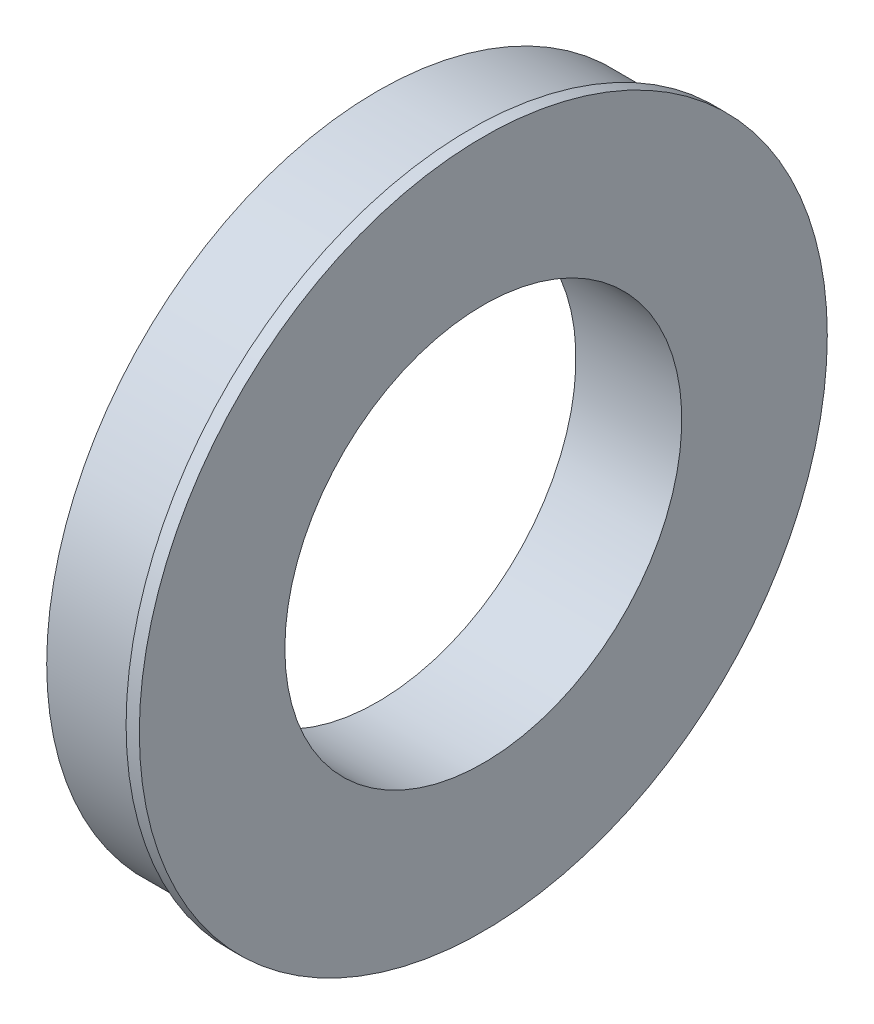
SolidWorks part; units mm, degrees
ref_plane "Front Plane" through (0, 0, 0) normal (0, 0, 1) x (1, 0, 0)
ref_plane "Top Plane" through (0, 0, 0) normal (0, 1, 0) x (1, 0, 0)
ref_plane "Right Plane" through (0, 0, 0) normal (1, 0, 0) x (0, 0, -1)
sketch "Sketch1" plane through (0, 0, 0) normal (1, 0, 0) x (0, 0, -1)
  circle A0 centre (0, 0) radius 38.1
  circle A1 centre (0, 0) radius 63.5
  dimension "D1" = 127
  dimension "D2" = 76.2
extrude "Boss-Extrude1" add sketch "Sketch1" along normal mid plane 19.05
sketch "Sketch2" plane through (9.525, 0, 0) normal (1, 0, 0) x (0, 0, -1)
  circle A0 centre (0, 0) radius 38.1 construction
  circle A1 centre (0, 0) radius 63.5
  circle A2 centre (0, 0) radius 63.5
  circle A3 centre (0, 0) radius 38.1
  circle A4 centre (0, 0) radius 66.04
  circle M3 centre (0, 0) radius 63.5
  circle M4 centre (0, 0) radius 38.1
  dimension "D2" = 132.08
  dimension "D1" = 0
extrude "Boss-Extrude2" add sketch "Sketch2" along normal mid plane 2.54 contours M3 M4 | A4 M3 | M4 | A2
sketch "Sketch4" plane through (8.255, 0, 0) normal (-1, 0, 0) x (0, 0, 1)
  circle A0 centre (0, 0) radius 38.1
extrude "Cut-Extrude1" cut sketch "Sketch4" against normal through all
